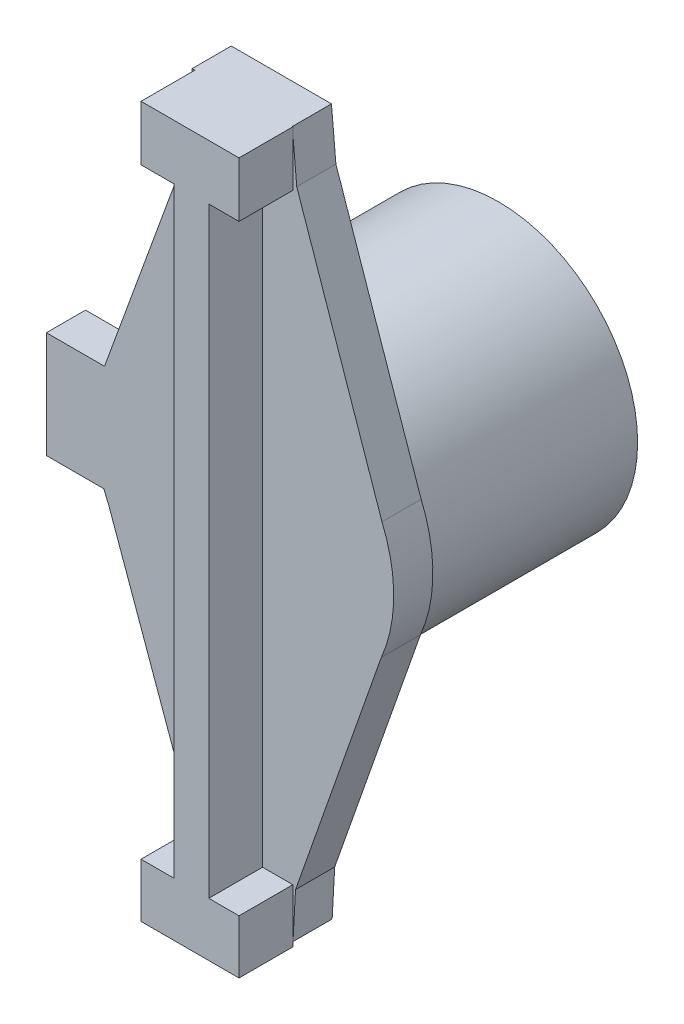
SolidWorks part; units mm, degrees
ref_plane "Front Plane" through (0, 0, 0) normal (0, 0, 1) x (1, 0, 0)
ref_plane "Top Plane" through (0, 0, 0) normal (0, 1, 0) x (1, 0, 0)
ref_plane "Right Plane" through (0, 0, 0) normal (1, 0, 0) x (0, 0, -1)
sketch "Sketch1" plane through (0, 0, 0) normal (0, 0, 1) x (1, 0, 0)
  circle A0 centre (0, 0) radius 0.0284
extrude "Boss-Extrude1" add sketch "Sketch1" along normal blind 0.044
sketch "Sketch2" plane through (0, 0, 0.044) normal (0, 0, 1) x (1, 0, 0)
  line L0 (-0.0285, 0.011) -> (-0.0106, 0.0602)
  line L1 (-0.0285, 0.011) -> (-0.0404, 0.011)
  line L3 (-0.0286, -0.0107) -> (-0.0404, -0.0107)
  line L4 (-0.0404, 0.011) -> (-0.0404, -0.0107)
  line L5 (-0.0106, 0.0602) -> (-0.0106, 0.0727)
  line L6 (-0.0106, 0.0727) -> (0.0099, 0.0727)
  line L7 (0.0099, 0.0727) -> (0.0108, 0.0624)
  line L8 (0.0108, 0.0624) -> (0.0282, 0.0119)
  line L9 (-0.0277, -0.0129) -> (-0.0112, -0.0588)
  line L10 (-0.0112, -0.0588) -> (-0.01, -0.0715)
  line L11 (-0.01, -0.0715) -> (0.01, -0.0715)
  line L12 (0.01, -0.0715) -> (0.0105, -0.062)
  line L13 (0.0105, -0.062) -> (0.028, -0.0122)
  arc A0 (-0.0286, -0.0107) -> (-0.0277, -0.0129) centre (0, 0) ccw
  arc A1 (0.028, -0.0122) -> (0.0282, 0.0119) centre (0, 0) ccw
extrude "Boss-Extrude2" add sketch "Sketch2" along normal blind 0.008
sketch "Sketch3" plane through (0, 0, 0.052) normal (0, 0, 1) x (1, 0, 0)
  line L0 (0.0099, 0.0727) -> (-0.0106, 0.0727) construction
  line L1 (-0.01, 0.0727) -> (0.01, 0.0727)
  line L2 (-0.01, 0.0727) -> (-0.01, 0.0614)
  line L3 (-0.01, 0.0614) -> (0.01, 0.0614)
  line L4 (0.01, 0.0727) -> (0.01, 0.0614)
  line L6 (-0.01, -0.0725) -> (0.01, -0.0725)
  line L7 (-0.01, -0.0725) -> (-0.01, -0.0614)
  line L8 (-0.01, -0.0614) -> (0.01, -0.0614)
  line L9 (0.01, -0.0725) -> (0.01, -0.0614)
extrude "Boss-Extrude3" add sketch "Sketch3" along normal blind 0.011
sketch "Sketch4" plane through (0, 0, 0.052) normal (0, 0, 1) x (1, 0, 0)
  line L0 (0.01, -0.0614) -> (-0.01, -0.0614) construction
  line L1 (-0.0033, -0.0614) -> (0.0038, -0.0614)
  line L2 (-0.0033, -0.0614) -> (-0.0033, 0.0614)
  line L3 (-0.0033, 0.0614) -> (0.0038, 0.0614)
  line L4 (0.0038, -0.0614) -> (0.0038, 0.0614)
  line L5 (-0.01, 0.0614) -> (0.01, 0.0614) construction
extrude "Boss-Extrude4" add sketch "Sketch4" along normal blind 0.011
